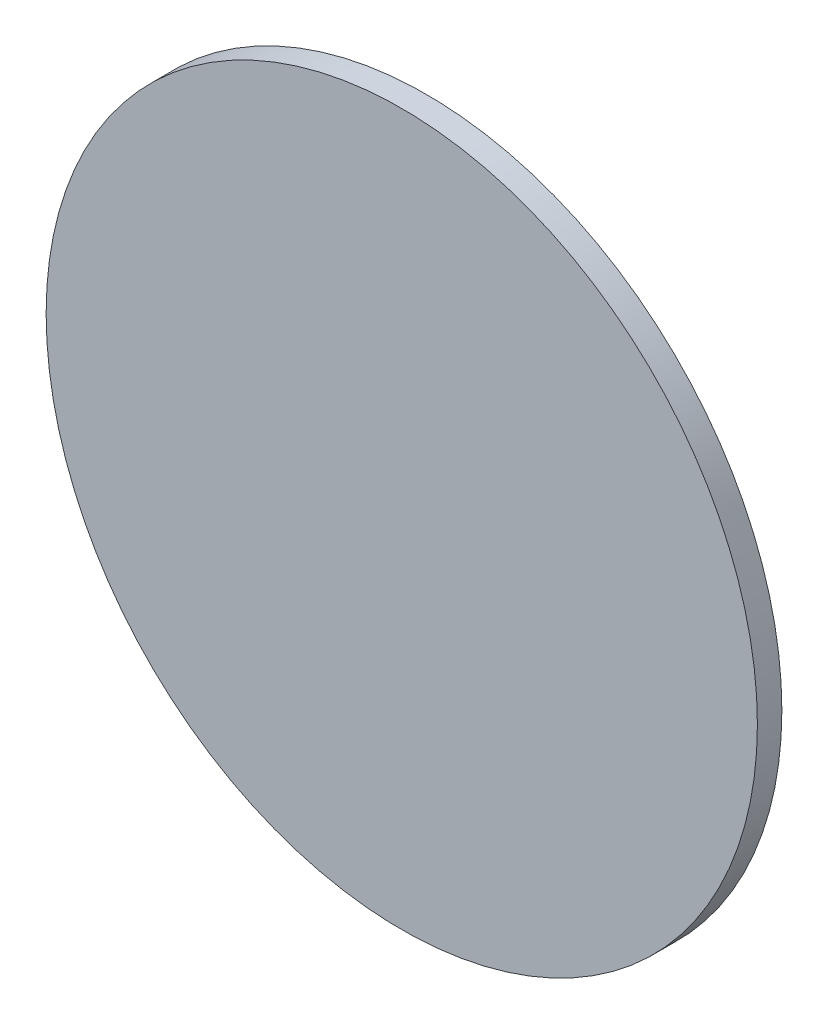
SolidWorks part; units mm, degrees
ref_plane "Front Plane" through (0, 0, 0) normal (0, 0, 1) x (1, 0, 0)
ref_plane "Top Plane" through (0, 0, 0) normal (0, 1, 0) x (1, 0, 0)
ref_plane "Right Plane" through (0, 0, 0) normal (1, 0, 0) x (0, 0, -1)
sketch "Sketch1" plane through (0, 0, 0) normal (0, 0, 1) x (1, 0, 0)
  circle A0 centre (0, 0) radius 36.9191
extrude "Boss-Extrude1" add sketch "Sketch1" along normal blind 2.54
